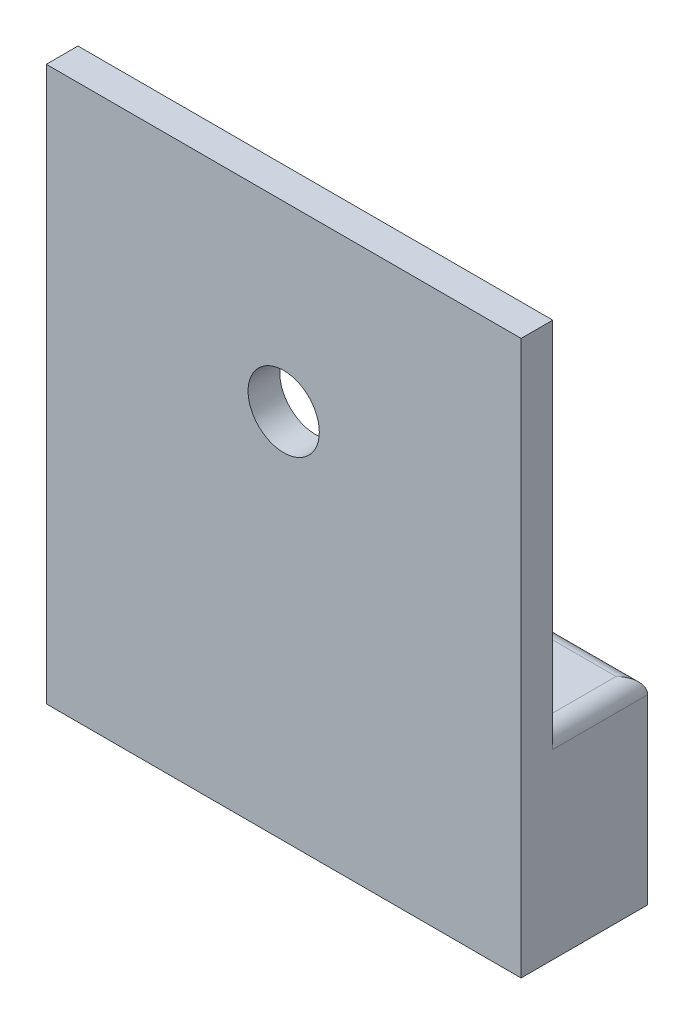
SolidWorks part; units mm, degrees
ref_plane "Front Plane" through (0, 0, 0) normal (0, 0, 1) x (1, 0, 0)
ref_plane "Top Plane" through (0, 0, 0) normal (0, 1, 0) x (1, 0, 0)
ref_plane "Right Plane" through (0, 0, 0) normal (1, 0, 0) x (0, 0, -1)
sketch "Sketch2" plane through (0, 0, 0) normal (0, 0, 1) x (1, 0, 0)
  line L0 (-41.0521, 24.3269) -> (18.9479, 24.3269)
  line L1 (18.9479, 24.3269) -> (18.9479, -45.6731)
  line L2 (18.9479, -45.6731) -> (-41.0521, -45.6731)
  line L3 (-41.0521, -45.6731) -> (-41.0521, 24.3269)
  line L4 (-73.5521, 1.3169) -> (51.4479, 1.3169) construction
  line L5 (-11.0521, 64.3646) -> (-11.0521, -61.7308) construction
  circle A0 centre (-11.0521, 1.3169) radius 4.5
  point P8 (-11.0521, 1.3169)
  point P9 (-11.0521, 1.3169)
  dimension "D3" = 9
  dimension "D1" = 60
  dimension "D2" = 70
  dimension "D4" = 30
  dimension "D5" = 23.01
extrude "Boss-Extrude1" add sketch "Sketch2" along normal blind 4
ref_plane "Plane1" through (0, 0, 0) normal (0, 0, -1) x (-1, 0, 0)
sketch "Sketch3" plane through (0, 0, 0) normal (0, 0, -1) x (-1, 0, 0)
  line L0 (-18.9479, -45.6731) -> (-18.9479, -20.6731)
  line L1 (-18.9479, -45.6731) -> (-18.9479, 24.3269) construction
  line L2 (-18.9479, -20.6731) -> (41.0521, -20.6731)
  line L3 (41.0521, 24.3269) -> (41.0521, -45.6731) construction
  line L4 (41.0521, -20.6731) -> (41.0521, -45.6731)
  line L5 (41.0521, -45.6731) -> (-18.9479, -45.6731)
  dimension "D1" = 25
extrude "Boss-Extrude2" add sketch "Sketch3" along normal blind 12
fillet "Fillet1" radius 2 3 edges at (18.9479, -20.6731, -6) (-41.0521, -20.6731, -6) (-11.0521, -20.6731, -12)
ref_plane "Plane2" through (0, -20.6731, 0) normal (0, 1, 0) x (1, 0, 0)
sketch "Sketch4" plane through (0, -20.6731, 0) normal (0, 1, 0) x (1, 0, 0)
  line L0 (16.9479, 5) -> (-39.0521, 5) construction
  line L1 (16.9479, 0) -> (16.9479, 10) construction
  line L2 (-39.0521, 10) -> (-39.0521, 0) construction
  line L3 (-29.0521, 10) -> (-29.0521, 0) construction
  line L4 (16.9479, 10) -> (-39.0521, 10) construction
  line L5 (25.85, 0) -> (-25.85, 0) construction
  line L6 (6.9479, 10) -> (6.9479, 0) construction
  line L7 (-39.0521, 0) -> (16.9479, 0) construction
  circle A0 centre (-29.0521, 5) radius 2.5
  circle A1 centre (6.9479, 5) radius 2.5
  dimension "D5" = 5
  dimension "D6" = 5
  dimension "D1" = 10
  dimension "D2" = 10
  dimension "D3" = 10
  dimension "D4" = 5
extrude "Cut-Extrude1" cut sketch "Sketch4" against normal blind 28
